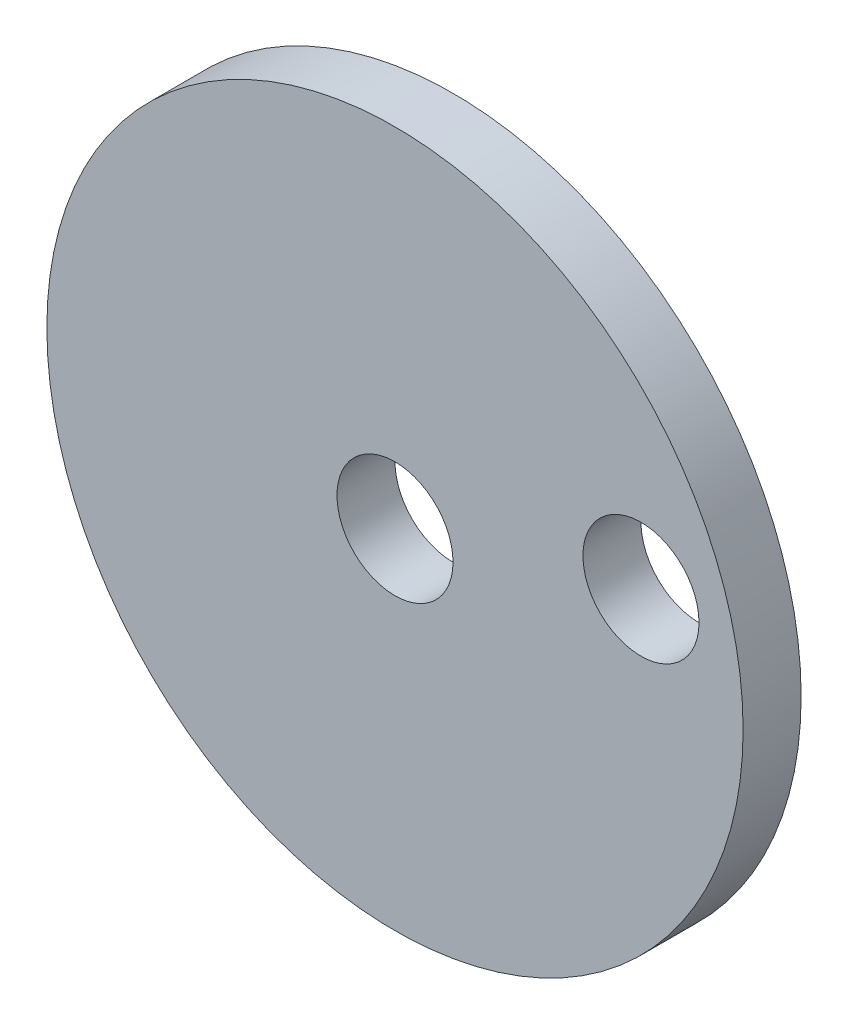
SolidWorks part; units mm, degrees
ref_plane "Front Plane" through (0, 0, 0) normal (0, 0, 1) x (1, 0, 0)
ref_plane "Top Plane" through (0, 0, 0) normal (0, 1, 0) x (1, 0, 0)
ref_plane "Right Plane" through (0, 0, 0) normal (1, 0, 0) x (0, 0, -1)
sketch "Sketch1" plane through (0, 0, 0) normal (0, 0, 1) x (1, 0, 0)
  circle A0 centre (0, 0) radius 38.1
  circle A1 centre (0, 0) radius 6.35
  circle A2 centre (26.9215, 7.7318) radius 6.35
  dimension "D1" = 76.2
  dimension "D2" = 12.7
  dimension "D3" = 12.7
extrude "Boss-Extrude1" add sketch "Sketch1" along normal blind 6.35
